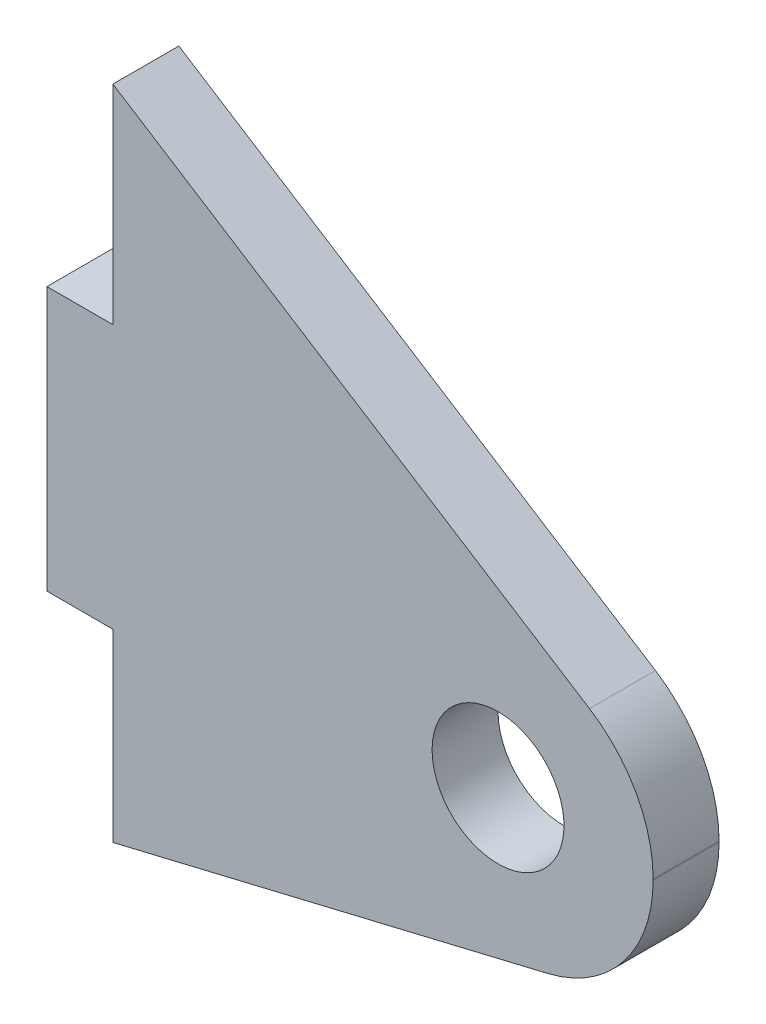
SolidWorks part; units mm, degrees
material "Custom Plastic"
ref_plane "X-Y Datum" through (0, 0, 0) normal (0, 0, 1) x (1, 0, 0)
ref_plane "X-Z Datum" through (0, 0, 0) normal (0, 1, 0) x (1, 0, 0)
ref_plane "Y-Z Datum" through (0, 0, 0) normal (1, 0, 0) x (0, 0, -1)
sketch "Sketch1" plane through (0, 0, 0) normal (0, 0, 1) x (1, 0, 0)
  line L0 (0, 0) -> (0, 50000) construction
  line L1 (0, 0) -> (50000, 0) construction
  line L2 (68.5482, 0) -> (68.5482, 64.9121)
  line L3 (68.5482, 64.9121) -> (0, 64.9121)
  line L4 (0, 64.9121) -> (0, 0)
  line L5 (0, 0) -> (68.5482, 0)
  dimension "D1" = 90
extrude "Boss-Extrude1" add sketch "Sketch1" along normal blind 3.175
hole_wizard "1/4 (0.25) Diameter Hole1" positions "Sketch2" profile "Sketch3" hole size "1/4" standard "ANSI Inch" end condition through all
sketch "Sketch2" plane through (0, 0, 0) normal (0, 0, -1) x (-1, 0, 0)
  line L0 (-68.5482, 64.9121) -> (0, 64.9121) construction
  line L1 (0, 64.9121) -> (0, 0) construction
  point P0 (-18.542, 44.8461)
  point P3 (-18.4869, 44.8647)
  dimension "D1" = 20.066
  dimension "D2" = 18.542
sketch "Sketch3" plane through (18.542, 44.8461, 0) normal (1, 0, 0) x (0, 1, 0)
  line L0 (0, 0) -> (0, 3.175)
  line L1 (0, 3.175) -> (3.175, 3.175)
  line L2 (3.175, 3.175) -> (3.175, 0)
  line L5 (3.175, 0) -> (0, 0)
  line L11 (0, -6.35) -> (0, 107.95) construction
  dimension "Thru Hole Dia." = 6.35
  dimension "Thru Hole Depth" = 3.175
sketch "Sketch4" plane through (0, 0, 0) normal (0, 0, -1) x (-1, 0, 0)
  line L0 (0, 64.9121) -> (-26.0096, 48.4021)
  line L1 (-26.0096, 48.4021) -> (-26.0096, 39.5121)
  line L2 (-26.0096, 39.5121) -> (0, 33.2931)
  line L3 (0, 64.9121) -> (0, 0) construction
  line L4 (0, 33.2931) -> (0, 64.9121)
  line L5 (0, 28.0016) -> (0, 34.8233) construction
  point P3 (-27.3941, 32.5614)
  point P8 (-27.3941, 55.3384)
  point P9 (-26.0096, 38.606)
  point P10 (0, 0)
  point P11 (0, 0)
  point P12 (0, 0)
  point P13 (-26.0096, 40.3581)
  point P14 (-26.0096, 39.5121)
  point P15 (-26.0096, 51.4838)
  point P16 (0, 36.9721)
  point P17 (-26.0096, 36.4641)
  point P18 (0, 0)
  point P19 (0, 0)
  point P21 (0, 0)
  point P22 (-26.0096, 38.2421)
  point P23 (-26.0096, 38.2421)
  point P24 (0, 33.4335)
  point P25 (-26.0096, 38.2421)
  point P26 (0, 0)
  point P27 (0, 0)
  point P28 (0, 0)
  point P29 (0, 0)
  point P30 (0, 0)
  line M6 (-68.5482, 0) -> (0, 0)
  line M7 (0, 0) -> (0, 64.9121)
  line M8 (0, 64.9121) -> (-68.5482, 64.9121)
  line M9 (-68.5482, 64.9121) -> (-68.5482, 0)
  dimension "D1" = 26.0096
  dimension "D3" = 8.89
  dimension "D4" = 16.51
extrude "Cut-Extrude1" cut sketch "Sketch4" against normal through all contours L2 L1 L0 M8 M9 M6 M7
fillet "Fillet1" radius 6.604 2 edges at (26.0096, 48.4021, 1.5875) (26.0096, 39.5121, 1.5875)
sketch "Sketch5" plane through (0, 0, 0) normal (0, 0, -1) x (-1, 0, 0)
  line L0 (0, 42.1831) -> (3.175, 42.1831)
  line L1 (0, 64.9121) -> (0, 33.2931) construction
  line L2 (3.175, 42.1831) -> (3.175, 54.8831)
  line L3 (3.175, 54.8831) -> (0, 54.8831)
  line L4 (0, 42.1831) -> (0, 54.8831)
  dimension "D1" = 3.175
  dimension "D2" = 12.7
  dimension "D3" = 8.89
extrude "Boss-Extrude2" add sketch "Sketch5" against normal blind 3.175
